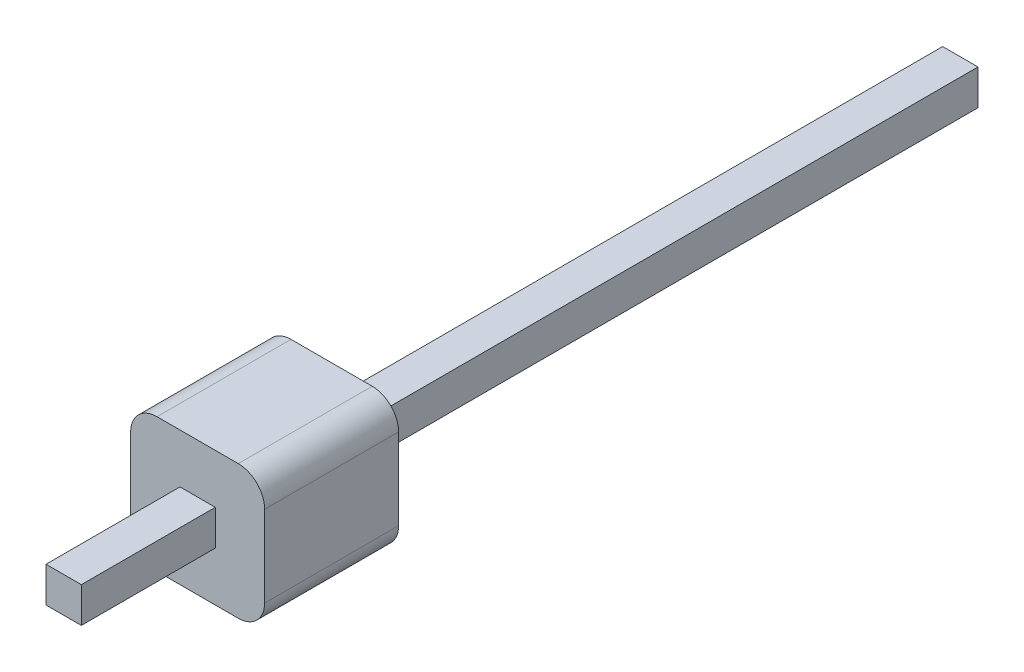
SolidWorks part; units mm, degrees
ref_plane "前视基准面" through (0, 0, 0) normal (0, 0, 1) x (1, 0, 0)
ref_plane "上视基准面" through (0, 0, 0) normal (0, 1, 0) x (1, 0, 0)
ref_plane "右视基准面" through (0, 0, 0) normal (1, 0, 0) x (0, 0, -1)
sketch "草图1" plane through (0, 0, 0) normal (0, 0, 1) x (1, 0, 0)
  line L0 (0, 5.3599) -> (0, -8.0108) construction
  line L1 (-1.27, 1.27) -> (1.27, 1.27)
  line L2 (-1.27, 1.27) -> (-1.27, -1.27)
  line L3 (-1.27, -1.27) -> (1.27, -1.27)
  line L4 (1.27, 1.27) -> (1.27, -1.27)
  line L5 (3.5018, 0) -> (-3.2993, 0) construction
  dimension "D1" = 2.54
  dimension "D2" = 2.54
extrude "拉伸1" add sketch "草图1" along normal blind 2.54
ref_plane "基准面1" through (0, 0, 5.08) normal (0, 0, -1) x (-1, 0, 0)
sketch "草图2" plane through (0, 0, 5.08) normal (0, 0, -1) x (-1, 0, 0)
  line L0 (-1.27, 0) -> (1.27, 0) construction
  line L1 (-1.27, -1.27) -> (-1.27, 1.27) construction
  line L2 (1.27, 1.27) -> (1.27, -1.27) construction
  line L3 (0, 1.9407) -> (0, -4.2425) construction
  line L5 (-0.335, 0.335) -> (0.335, 0.335)
  line L6 (-0.335, 0.335) -> (-0.335, -0.335)
  line L7 (-0.335, -0.335) -> (0.335, -0.335)
  line L8 (0.335, 0.335) -> (0.335, -0.335)
  dimension "D1" = 0.67
  dimension "D2" = 0.67
sketch "草图3" plane through (0, 0, 0) normal (1, 0, 0) x (0, 0, -1)
  line L0 (11.92, -0.01) -> (-5.08, -0.01)
  line L1 (-5.08, 1.9407) -> (-5.08, -4.2425) construction
  line L8 (-2.54, 1.27) -> (0, 1.27) construction
  line L9 (0, -1.27) -> (0, 1.27) construction
  point P11 (2.54, -1.2991)
  dimension "D1" = 5.08
  dimension "D2" = 17
  dimension "D4" = 1.28
sweep "扫描1" add profiles "草图2" path "草图3"
fillet "圆角1" radius 0.5 4 edges at (1.27, 1.27, 1.27) (1.27, -1.27, 1.27) (-1.27, -1.27, 1.27) (-1.27, 1.27, 1.27)
